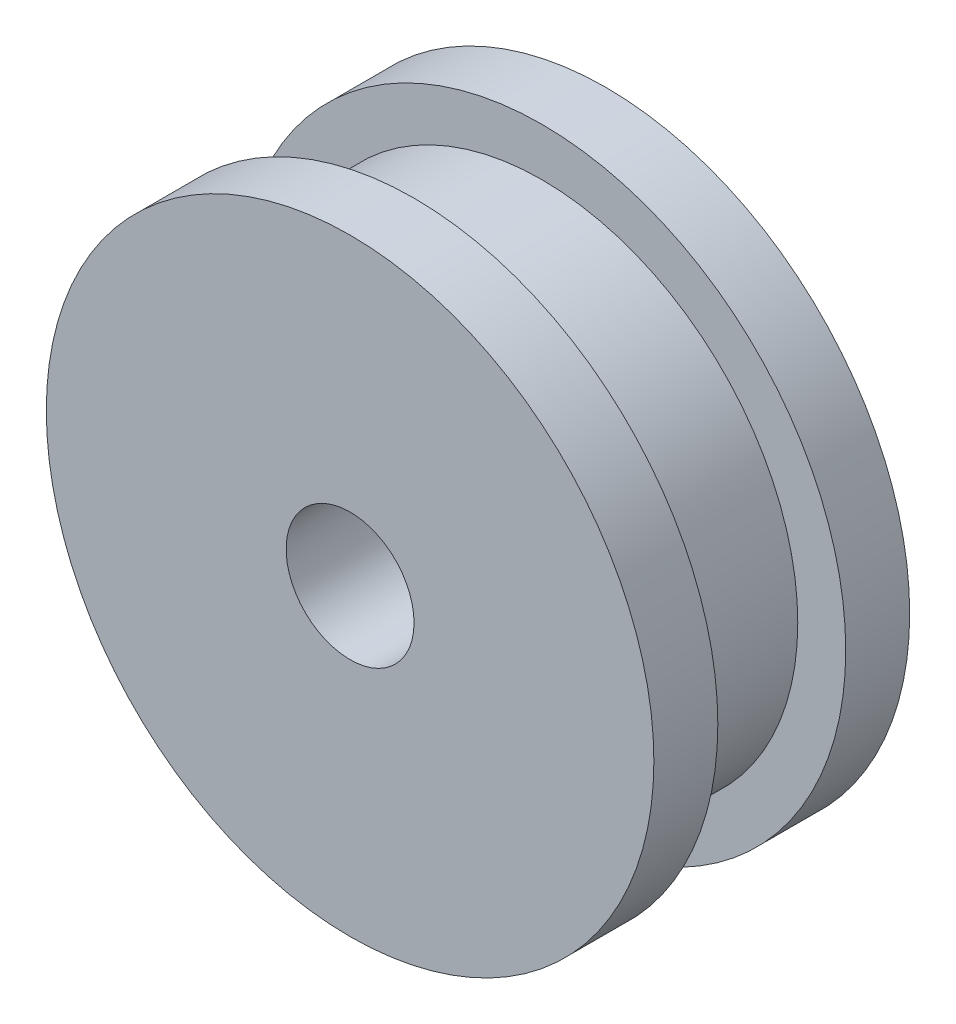
SolidWorks part; units mm, degrees
material "PE High Density"
ref_plane "Front Plane" through (0, 0, 0) normal (0, 0, 1) x (1, 0, 0)
ref_plane "Top Plane" through (0, 0, 0) normal (0, 1, 0) x (1, 0, 0)
ref_plane "Right Plane" through (0, 0, 0) normal (1, 0, 0) x (0, 0, -1)
sketch "Sketch1" plane through (0, 0, 0) normal (0, 0, 1) x (1, 0, 0)
  circle A0 centre (0, 0) radius 4
  dimension "D1" = 8
extrude "Boss-Extrude1" add sketch "Sketch1" along normal mid plane 2
sketch "Sketch3" plane through (0, 0, 1) normal (0, 0, 1) x (1, 0, 0)
  circle A0 centre (0, 0) radius 4.75
  dimension "D1" = 9.5
extrude "Boss-Extrude3" add sketch "Sketch3" along normal blind 1
mirror "Mirror1" about plane through (0, 0, 0) normal (0, 0, 1) of "Boss-Extrude3"
sketch "Sketch4" plane through (0, 0, 2) normal (0, 0, 1) x (1, 0, 0)
  circle A0 centre (0, 0) radius 1
  dimension "D1" = 2
extrude "Cut-Extrude1" cut sketch "Sketch4" against normal through all
